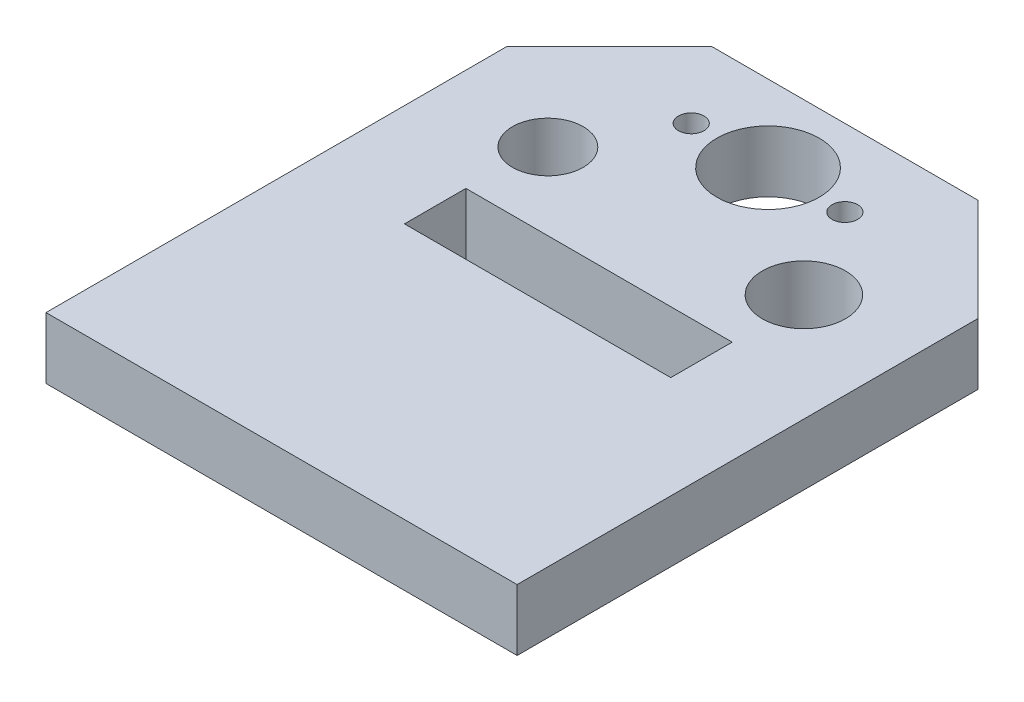
SolidWorks part; units mm, degrees
material "HDPE-green"
ref_plane "Front Plane" through (0, 0, 0) normal (0, 0, 1) x (1, 0, 0)
ref_plane "Top Plane" through (0, 0, 0) normal (0, 1, 0) x (1, 0, 0)
ref_plane "Right Plane" through (0, 0, 0) normal (1, 0, 0) x (0, 0, -1)
sketch "Sketch1" plane through (0, 0, 0) normal (0, 1, 0) x (1, 0, 0)
  line L1 (-46, 55) -> (46, 55)
  line L2 (-46, 55) -> (-46, -55)
  line L3 (-46, -55) -> (46, -55)
  line L4 (46, 55) -> (46, -55)
  line L5 (-46, 55) -> (46, -55) construction
  line L6 (-46, -55) -> (46, 55) construction
  point P0 (0, 0)
  dimension "D1" = 110
  dimension "D2" = 92
extrude "Boss-Extrude1" add sketch "Sketch1" along normal blind 12
sketch "Sketch2" plane through (0, 12, 0) normal (0, 1, 0) x (1, 0, 0)
  line L0 (0, -11.1414) -> (0, 34.2756) construction
  line L1 (46, 55) -> (-46, 55) construction
  line L2 (-20.0177, 40) -> (14.269, 40) construction
  circle A0 centre (0, 40) radius 10
  circle A1 centre (-25, 22) radius 6.9023
  circle A2 centre (25, 22) radius 8.1155
  circle A3 centre (-15, 40) radius 2.5
  circle A4 centre (15, 40) radius 2.5
  dimension "D1" = 20
  dimension "D2" = 25
  dimension "D3" = 18
  dimension "D4" = 25
  dimension "D5" = 18
  dimension "D6" = 15
  dimension "D7" = 5
  dimension "D8" = 5
  dimension "D9" = 15
  dimension "D10" = 15
extrude "Cut-Extrude1" cut sketch "Sketch2" against normal up to next
sketch "Sketch3" plane through (0, 12, 0) normal (0, 1, 0) x (1, 0, 0)
  line L0 (0, 0) -> (0, -27.5305) construction
  line L1 (26, -5) -> (-26, -5)
  line L2 (26, -5) -> (26, 7)
  line L3 (26, 7) -> (-26, 7)
  line L4 (-26, -5) -> (-26, 7)
  line L5 (26, -5) -> (-26, 7) construction
  line L6 (26, 7) -> (-26, -5) construction
  circle A0 centre (0, 40) radius 10 construction
  point P0 (0, 1)
  dimension "D1" = 33
  dimension "D2" = 12
  dimension "D3" = 52
extrude "Cut-Extrude2" cut sketch "Sketch3" against normal up to next
chamfer "Chamfer1" distance 20 angle 45 2 edges at (46, 6, -55) (-46, 6, -55)
